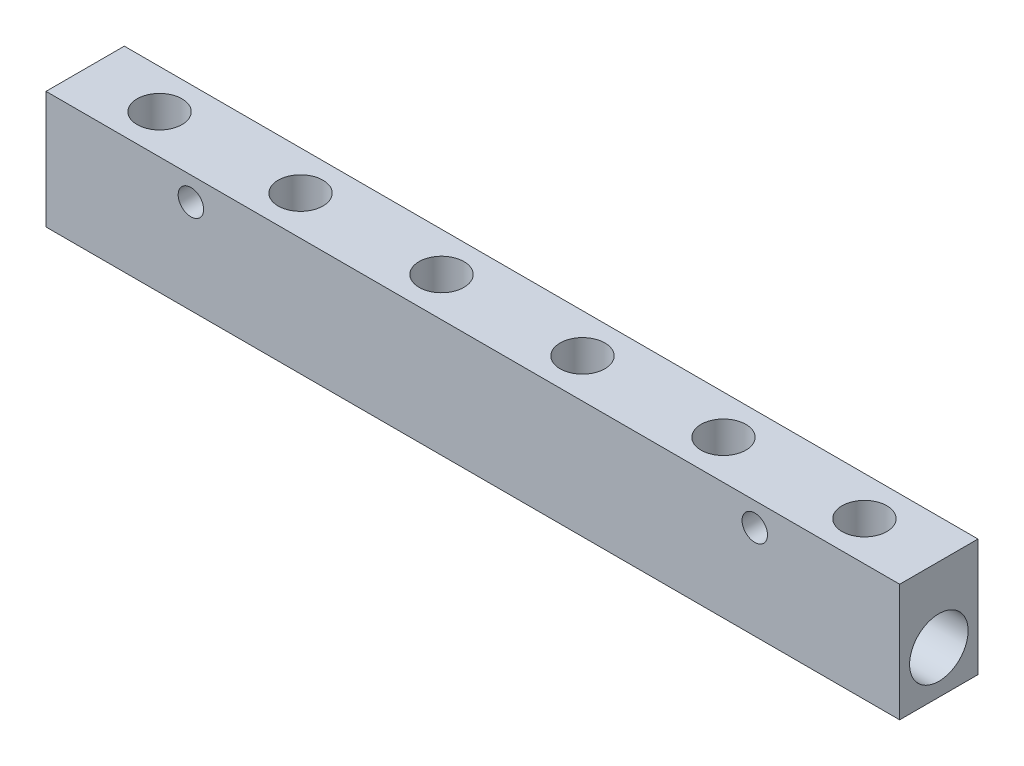
SolidWorks part; units mm, degrees
ref_plane "Front Plane" through (0, 0, 0) normal (0, 0, 1) x (1, 0, 0)
ref_plane "Top Plane" through (0, 0, 0) normal (0, 1, 0) x (1, 0, 0)
ref_plane "Right Plane" through (0, 0, 0) normal (1, 0, 0) x (0, 0, -1)
sketch "Sketch1" plane through (0, 0, 0) normal (0, 1, 0) x (1, 0, 0)
  line L1 (-109, -10) -> (109, -10)
  line L2 (-109, -10) -> (-109, 10)
  line L3 (-109, 10) -> (109, 10)
  line L4 (109, -10) -> (109, 10)
  line L5 (-109, -10) -> (109, 10) construction
  line L6 (-109, 10) -> (109, -10) construction
  point P0 (0, 0)
  dimension "D1" = 218
  dimension "D2" = 20
extrude "Boss-Extrude1" add sketch "Sketch1" along normal blind 30
sketch "Sketch2" plane through (0, 0, 10) normal (0, 0, 1) x (1, 0, 0)
  line L0 (-109, 30) -> (109, 30) construction
  line L1 (-109, 30) -> (-109, 0) construction
  line L2 (109, 30) -> (109, 0) construction
  circle A0 centre (-72, 24) radius 3.25
  circle A1 centre (72, 24) radius 3.25
  dimension "D1" = 6
  dimension "D3" = 6.5
  dimension "D4" = 6.5
  dimension "D2" = 37
  dimension "D5" = 37
  dimension "D6" = 6
extrude "Cut-Extrude1" cut sketch "Sketch2" against normal blind 30
sketch "Sketch3" plane through (-109, 0, 0) normal (-1, 0, 0) x (0, 0, 1)
  line L4 (-10, 0) -> (10, 0) construction
  circle A1 centre (0, 11) radius 7.475
  dimension "D1" = 14.95
  dimension "D2" = 11
extrude "Cut-Extrude2" cut sketch "Sketch3" against normal through all
sketch "Sketch4" plane through (0, 30, 0) normal (0, 1, 0) x (1, 0, 0)
  line L0 (-109, 10) -> (-109, -10) construction
  line L1 (109, 10) -> (-109, 10) construction
  line L2 (109, -10) -> (109, 10) construction
  line L3 (-109, -10) -> (109, -10) construction
  circle A0 centre (-90, 0) radius 5.7225
  circle A2 centre (-54, 0) radius 5.7225
  circle A3 centre (-18, 0) radius 5.7225
  circle A4 centre (90, 0) radius 5.7225
  circle A5 centre (18, 0) radius 5.7225
  circle A6 centre (54, 0) radius 5.7225
  dimension "D2" = 11.445
  dimension "D4" = 11.445
  dimension "D5" = 11.445
  dimension "D6" = 11.445
  dimension "D13" = 11.445
  dimension "D14" = 11.445
  dimension "D1" = 19
  dimension "D3" = 10
  dimension "D7" = 19
  dimension "D8" = 10
  dimension "D9" = 10
  dimension "D10" = 10
  dimension "D11" = 36
  dimension "D12" = 36
  dimension "D15" = 10
  dimension "D16" = 10
  dimension "D17" = 36
  dimension "D18" = 36
extrude "Cut-Extrude3" cut sketch "Sketch4" against normal blind 15
